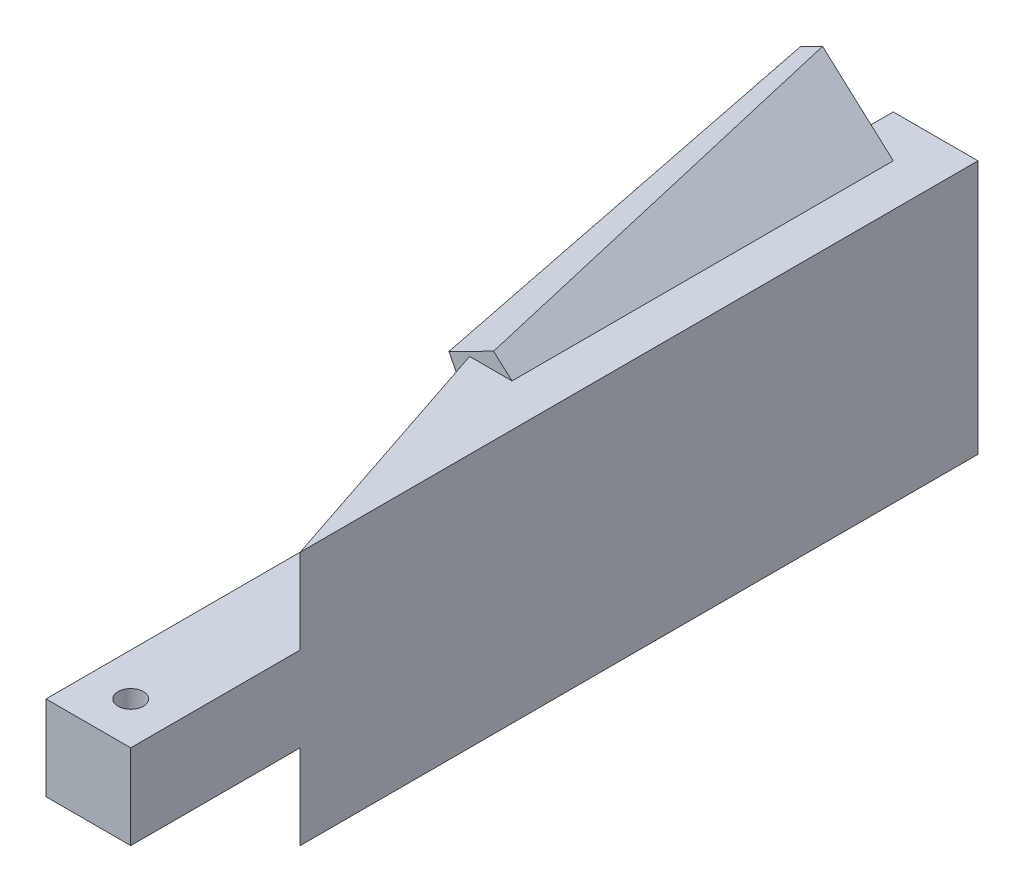
SolidWorks part; units mm, degrees
ref_plane "Alzado" through (0, 0, 0) normal (0, 0, 1) x (1, 0, 0)
ref_plane "Planta" through (0, 0, 0) normal (0, 1, 0) x (1, 0, 0)
ref_plane "Vista lateral" through (0, 0, 0) normal (1, 0, 0) x (0, 0, -1)
sketch "Croquis1" plane through (0, 0, 0) normal (0, 0, 1) x (1, 0, 0)
  line L1 (-22.5, -10) -> (22.5, -10)
  line L2 (-22.5, -10) -> (-22.5, 5)
  line L3 (-22.5, 5) -> (22.5, 5)
  line L4 (22.5, -10) -> (22.5, 5)
  circle A0 centre (0, 0) radius 55
  dimension "D1" = 110
  dimension "D2" = 10
  dimension "D3" = 5
  dimension "D4" = 45
  dimension "D5" = 22.5
extrude "Saliente-Extruir1" add sketch "Croquis1" along normal blind 10
sketch "Croquis2" plane through (0, 0, 10) normal (0, 0, 1) x (1, 0, 0)
  line L0 (-69.3522, 0) -> (69.121, 0) construction
  line L1 (0, 62.8793) -> (0, -67.9652) construction
  line L3 (25, -15) -> (35, -15)
  line L4 (25, -15) -> (25, 15)
  line L5 (25, 15) -> (35, 15)
  line L6 (35, -15) -> (35, 15)
  line L7 (25, -15) -> (35, 15) construction
  line L8 (25, 15) -> (35, -15) construction
  point P5 (30, 0)
  dimension "D1" = 30
  dimension "D2" = 35
  dimension "D3" = 10
extrude "Saliente-Extruir2" add sketch "Croquis2" along normal blind 95
sketch "Croquis3" plane through (0, -15, 0) normal (0, -1, 0) x (1, 0, 0)
  line L0 (25, 105) -> (35, 105) construction
  line L1 (25, 105) -> (25, 10) construction
  circle A0 centre (30, 100) radius 1.5
  dimension "D1" = 3
  dimension "D2" = 5
  dimension "D3" = 5
extrude "Cortar-Extruir1" cut sketch "Croquis3" against normal blind 50
sketch "Croquis4" plane through (0, -15, 0) normal (0, -1, 0) x (1, 0, 0)
  line L0 (35, 85) -> (25, 55)
  line L2 (25, 95) -> (25, 105)
  line L3 (25, 105) -> (35, 105)
  line L4 (35, 85) -> (35, 105)
  line L7 (25, 105) -> (25, 10) construction
  line L8 (25, 55) -> (25, 95)
  point P0 (30, 100)
  dimension "D1" = 50
  dimension "D2" = 20
extrude "Cortar-Extruir2" cut sketch "Croquis4" against normal blind 10
mirror "Simetría1" about plane through (0, 0, 0) normal (0, 1, 0) of "Cortar-Extruir2"
sketch "Croquis5" plane through (0, 5, 0) normal (0, -1, 0) x (1, 0, 0)
  line L0 (55, 10) -> (-55, 10) construction
  circle A0 centre (0, 5) radius 2.5
  dimension "D1" = 5
  dimension "D2" = 5
extrude "Cortar-Extruir3" cut sketch "Croquis5" against normal mid plane 170
sketch "Croquis6" plane through (0, 0, 10) normal (0, 0, 1) x (1, 0, 0)
  line L0 (0, 0) -> (0, 230.7937) construction
  line L1 (-2.5, 48.5) -> (2.5, 48.5) construction
  line L2 (-6, 21.6) -> (6, 21.6)
  line L3 (-6, 21.6) -> (-6, 53.6)
  line L4 (-6, 53.6) -> (6, 53.6)
  line L5 (6, 21.6) -> (6, 53.6)
  line L6 (-6, 21.6) -> (6, 53.6) construction
  line L7 (-6, 53.6) -> (6, 21.6) construction
  line L8 (0, 0) -> (0, -76.3571) construction
  line L9 (-20, -34.75) -> (20, -34.75) construction
  line L10 (-20, -10) -> (20, -10)
  line L11 (-20, -10) -> (-20, -5)
  line L12 (-20, -5) -> (20, -5)
  line L13 (20, -10) -> (20, -5)
  line L14 (-20, -10) -> (20, -5) construction
  line L15 (-20, -5) -> (20, -10) construction
  line L16 (-6, -59.5) -> (6, -59.5)
  line L17 (-6, -59.5) -> (-6, -10)
  line L18 (-6, -10) -> (6, -10)
  line L19 (6, -59.5) -> (6, -10)
  line L20 (-6, -59.5) -> (6, -10) construction
  line L21 (-6, -10) -> (6, -59.5) construction
  circle A0 centre (0, 48.5) radius 2.5
  circle A4 centre (0, 48.5) radius 2.5 construction
  point P3 (0, 37.6)
  point P15 (0, -7.5)
  point P22 (0, -34.75)
  dimension "D3" = 5
  dimension "D1" = 32
  dimension "D2" = 12
  dimension "D4" = 5.1
  dimension "D5" = 40
  dimension "D6" = 5
  dimension "D7" = 7.5
  dimension "D8" = 49.5
sketch "Croquis7" plane through (0, 0, 10) normal (0, 0, 1) x (1, 0, 0)
  line L1 (0, 0) -> (0, 70.4591) construction
  line L2 (0, 0) -> (0, 230.7937) construction
  circle A0 centre (0, 48.5) radius 2.5
  dimension "D1" = 5
  dimension "D2" = 48.5
extrude "Saliente-Extruir3" add sketch "Croquis7" along normal blind 5
sketch "Croquis8" plane through (0, 0, 10) normal (0, 0, 1) x (1, 0, 0)
  line L0 (0, 37.6) -> (20.0888, 37.6) construction
  line L1 (0, 0) -> (0, 230.7937) construction
  line L2 (9, 39.8913) -> (9, 38.6)
  line L3 (10, 42.2518) -> (10, 30.3281) construction
  line L4 (7.7087, 36.6) -> (9, 36.6)
  line L5 (11, 39.8913) -> (11, 38.6)
  line L6 (7.7087, 38.6) -> (9, 38.6)
  line L7 (9, 36.6) -> (9, 35.3087)
  line L8 (11, 36.6) -> (12.2913, 36.6)
  line L9 (11, 38.6) -> (12.2913, 38.6)
  line L10 (11, 36.6) -> (11, 35.3087)
  line L11 (0, 59.2687) -> (0, 20.199) construction
  line L12 (-7.7087, 36.6) -> (-9, 36.6)
  line L13 (-7.7087, 38.6) -> (-9, 38.6)
  line L14 (-9, 39.8913) -> (-9, 38.6)
  line L15 (-11, 39.8913) -> (-11, 38.6)
  line L16 (-11, 38.6) -> (-12.2913, 38.6)
  line L17 (-11, 36.6) -> (-12.2913, 36.6)
  line L18 (-11, 36.6) -> (-11, 35.3087)
  line L19 (-9, 36.6) -> (-9, 35.3087)
  line L20 (0, 0) -> (0, -49.9896) construction
  line L21 (0, 0) -> (0, -76.3571) construction
  line L22 (0, -34.75) -> (-20, -34.75) construction
  line L23 (-20, -34.75) -> (20, -34.75) construction
  line L24 (-7.7087, -35.75) -> (-9, -35.75)
  line L25 (-7.7087, -33.75) -> (-9, -33.75)
  line L26 (-9, -32.4587) -> (-9, -33.75)
  line L27 (-11, -32.4587) -> (-11, -33.75)
  line L28 (-11, -33.75) -> (-12.2913, -33.75)
  line L29 (-11, -35.75) -> (-12.2913, -35.75)
  line L30 (-11, -35.75) -> (-11, -37.0413)
  line L31 (-9, -35.75) -> (-9, -37.0413)
  line L32 (9, -35.75) -> (9, -37.0413)
  line L33 (11, -35.75) -> (11, -37.0413)
  line L34 (11, -35.75) -> (12.2913, -35.75)
  line L35 (11, -33.75) -> (12.2913, -33.75)
  line L36 (11, -32.4587) -> (11, -33.75)
  line L37 (9, -32.4587) -> (9, -33.75)
  line L38 (7.7087, -33.75) -> (9, -33.75)
  line L39 (7.7087, -35.75) -> (9, -35.75)
  arc A0 (12.2913, 36.6) -> (12.2913, 38.6) centre (10, 37.6) ccw
  arc A1 (9, 35.3087) -> (11, 35.3087) centre (10, 37.6) ccw
  arc A2 (7.7087, 38.6) -> (7.7087, 36.6) centre (10, 37.6) ccw
  arc A3 (11, 39.8913) -> (9, 39.8913) centre (10, 37.6) ccw
  arc A4 (-7.7087, 38.6) -> (-7.7087, 36.6) centre (-10, 37.6) cw
  arc A5 (-11, 39.8913) -> (-9, 39.8913) centre (-10, 37.6) cw
  arc A6 (-12.2913, 36.6) -> (-12.2913, 38.6) centre (-10, 37.6) cw
  arc A7 (-9, 35.3087) -> (-11, 35.3087) centre (-10, 37.6) cw
  arc A8 (-7.7087, -33.75) -> (-7.7087, -35.75) centre (-10, -34.75) cw
  arc A9 (-11, -32.4587) -> (-9, -32.4587) centre (-10, -34.75) cw
  arc A10 (-12.2913, -35.75) -> (-12.2913, -33.75) centre (-10, -34.75) cw
  arc A11 (-9, -37.0413) -> (-11, -37.0413) centre (-10, -34.75) cw
  arc A12 (9, -37.0413) -> (11, -37.0413) centre (10, -34.75) ccw
  arc A13 (12.2913, -35.75) -> (12.2913, -33.75) centre (10, -34.75) ccw
  arc A14 (11, -32.4587) -> (9, -32.4587) centre (10, -34.75) ccw
  arc A15 (7.7087, -33.75) -> (7.7087, -35.75) centre (10, -34.75) ccw
  dimension "D1" = 5
  dimension "D2" = 10
  dimension "D3" = 1
  dimension "D4" = 1
  dimension "D5" = 10
extrude "Cortar-Extruir4" cut sketch "Croquis8" against normal blind 10
sketch "Croquis10" plane through (0, 0, 0) normal (0, 1, 0) x (1, 0, 0)
  line L0 (0, 0) -> (0, -45.7171) construction
  line L2 (-55, 0) -> (-55, -10) construction
  line L3 (55, 0) -> (-55, 0) construction
  line L4 (-55, -10) -> (55, -10) construction
  circle A0 centre (-55, -5) radius 2.575
  dimension "D1" = 5.15
revolve "Cortar-Revolución1" cut sketch "Croquis10" angle 360 about L0
sketch "Croquis11" plane through (0, 15, 0) normal (0, 1, 0) x (1, 0, 0)
  line L0 (35, -10) -> (25, -10) construction
  line L1 (35, -105) -> (25, -105)
  line L2 (35, -105) -> (35, -5)
  line L3 (35, -5) -> (25, -5)
  line L4 (25, -105) -> (25, -5)
  dimension "D1" = 5
extrude "Cortar-Extruir5" cut sketch "Croquis11" against normal mid plane 211 flip side to cut
sketch "Croquis12" plane through (0, 0, 10) normal (0, 0, 1) x (1, 0, 0)
  line L1 (25, 15) -> (35, 15)
  line L2 (25, 15) -> (25, -15)
  line L3 (25, -15) -> (35, -15)
  line L4 (35, 15) -> (35, -15)
extrude "Cortar-Extruir6" cut sketch "Croquis12" against normal blind 10 flip side to cut
ref_plane "Plano1" through (25, 15, 5) normal (0, 0, -1) x (-1, 0, 0)
ref_plane "Plano2" through (25, -15, 5) normal (0, 1, 0) x (1, 0, 0)
sketch "Croquis15" plane through (0, 0, 5) normal (0, 0, -1) x (-1, 0, 0)
  line L0 (-35, 0) -> (-25, 15) construction
  line L1 (-35, -15) -> (-35, 15) construction
  line L2 (-25, 15) -> (-19.0641, 23.9038) construction
  line L3 (-35, 0) -> (-14.156, 0) construction
  line L4 (-30, 15) -> (-20.8775, 23.2307)
  line L5 (-25, 15) -> (-35, 15) construction
  line L6 (-20.8775, 23.2307) -> (-19.0641, 21.2209)
  line L7 (-19.0641, 21.2209) -> (-25, 9.4582)
  line L8 (-25, -15) -> (-25, 15) construction
  line L9 (-25, 9.4582) -> (-30, 15)
extrude "Saliente-Extruir4" add sketch "Croquis15" against normal blind 50
ref_plane "Plano3" through (25, 9.4582, 5) normal (0, 0, -1) x (-1, 0, 0)
sketch "Croquis17" plane through (23.7299, 11.975, 0) normal (-0.8928, -0.4505, 0) x (0, 0, 1)
  line L0 (55, 2.5998) -> (10, 10.3564)
  line L1 (55, -2.8191) -> (55, 10.3564) construction
  line L2 (55, 2.5998) -> (58.2994, 13.534)
  line L3 (32.7076, 13.534) -> (-8.0932, 24.4407)
  line L5 (55, 10.3564) -> (5, 10.3564) construction
  line L6 (58.2994, 13.534) -> (32.7076, 13.534)
  line L7 (10, 10.3564) -> (-8.0932, 24.4407)
  line L9 (5, -2.8191) -> (5, 10.3564) construction
  dimension "D1" = 5
extrude "Cortar-Extruir7" cut sketch "Croquis17" against normal blind 30
mirror "Simetría2" about plane through (0, 0, 0) normal (0, 1, 0) of "Saliente-Extruir4", "Cortar-Extruir7"
sketch "Croquis18" plane through (0, 0, 5) normal (0, 0, -1) x (-1, 0, 0)
  line L1 (-35, 15) -> (-25, 15)
  line L2 (-35, 15) -> (-35, -15)
  line L3 (-35, -15) -> (-25, -15)
  line L4 (-25, 15) -> (-25, -15)
  dimension "D1" = 10
  dimension "D2" = 30
extrude "Cortar-Extruir8" cut sketch "Croquis18" against normal blind 5 flip side to cut
